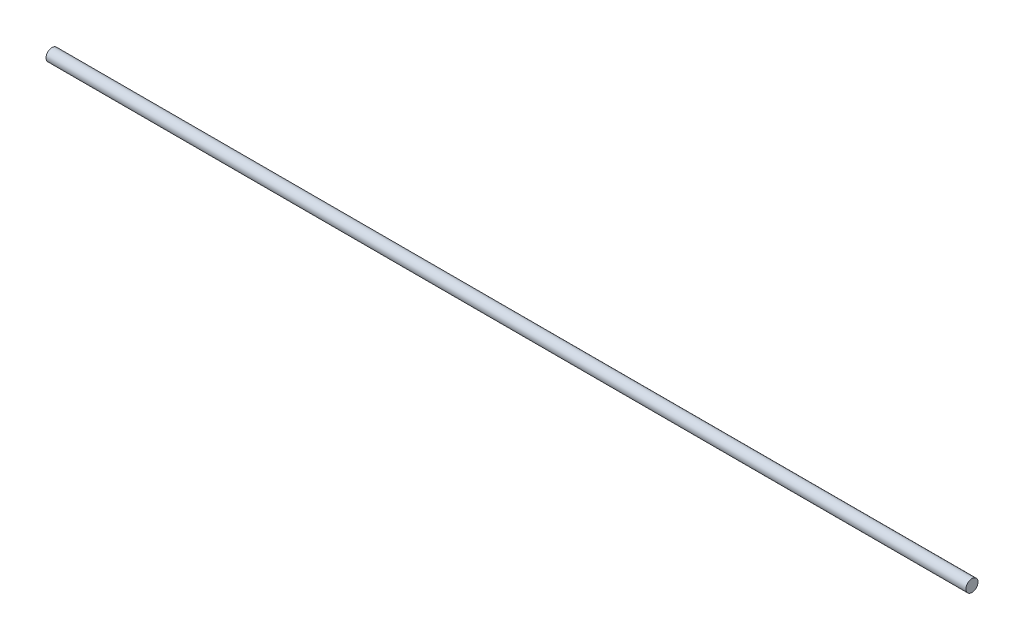
SolidWorks part; units mm, degrees
ref_plane "Front Plane" through (0, 0, 0) normal (0, 0, 1) x (1, 0, 0)
ref_plane "Top Plane" through (0, 0, 0) normal (0, 1, 0) x (1, 0, 0)
ref_plane "Right Plane" through (0, 0, 0) normal (1, 0, 0) x (0, 0, -1)
sketch "Sketch1" plane through (0, 0, 0) normal (1, 0, 0) x (0, 0, -1)
  circle A0 centre (0, 0) radius 6
extrude "Boss-Extrude1" add sketch "Sketch1" along normal mid plane 914.4
